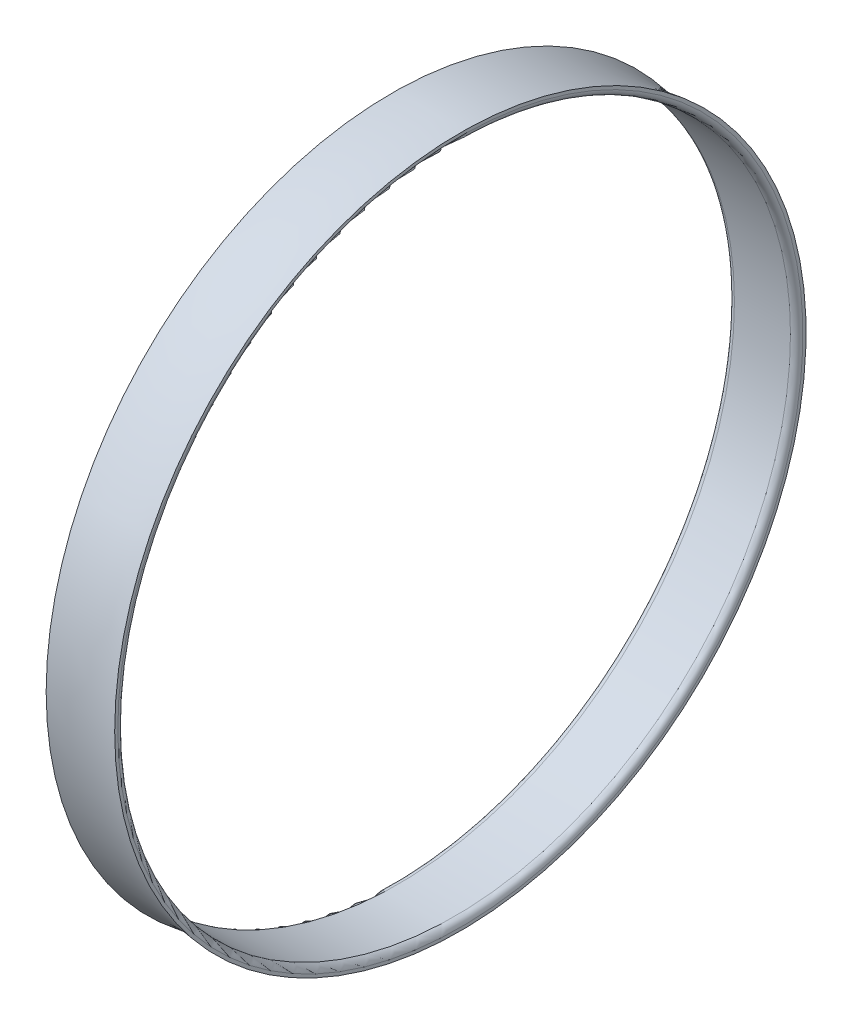
SolidWorks part; units mm, degrees
ref_plane "Płaszczyzna przednia" through (0, 0, 0) normal (0, 0, 1) x (1, 0, 0)
ref_plane "Płaszczyzna górna" through (0, 0, 0) normal (0, 1, 0) x (1, 0, 0)
ref_plane "Płaszczyzna prawa" through (0, 0, 0) normal (1, 0, 0) x (0, 0, -1)
sketch "Szkic1" plane through (0, 0, 0) normal (0, 0, 1) x (1, 0, 0)
  line L1 (5.7856, 53.9972) -> (14.7856, 53.9972)
  line L3 (-59.6339, 0) -> (89.1799, 0) construction
  line L15 (4.7856, 58.8508) -> (4.7856, 52.4763) construction
  line L16 (15.7856, 56.7161) -> (15.7856, 49.8699) construction
  line L17 (4.7856, 55.5) -> (4.7856, 54.9972)
  line L18 (15.7856, 55.5) -> (15.7856, 54.9972)
  line L19 (4.7856, -55) -> (4.7856, 55) construction
  arc A0 (15.7856, 55.5) -> (4.7856, 55.5) centre (10.2856, 84.9915) cw
  arc A6 (4.7856, 54.9972) -> (5.7856, 53.9972) centre (5.7856, 54.9972) ccw
  arc A7 (14.7856, 53.9972) -> (15.7856, 54.9972) centre (14.7856, 54.9972) ccw
  dimension "D2" = 55.5
  dimension "D3" = 11
  dimension "D4" = 0.5028
  dimension "D5" = 9
revolve "Obrót1" add sketch "Szkic1" angle 360 about L3
